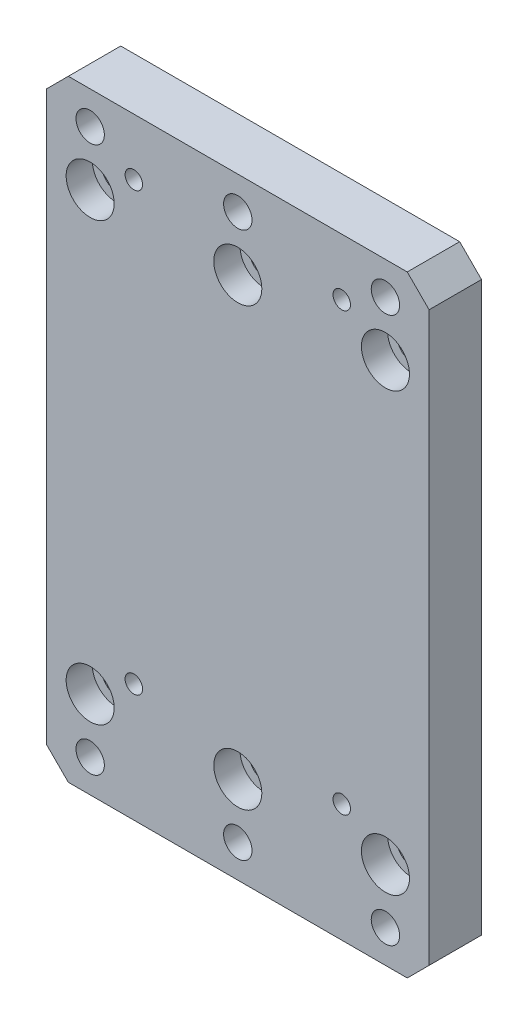
SolidWorks part; units mm, degrees
ref_plane "前视基准面" through (0, 0, 0) normal (0, 0, 1) x (1, 0, 0)
ref_plane "上视基准面" through (0, 0, 0) normal (0, 1, 0) x (1, 0, 0)
ref_plane "右视基准面" through (0, 0, 0) normal (1, 0, 0) x (0, 0, -1)
sketch "草图1" plane through (0, 0, 0) normal (0, 0, 1) x (1, 0, 0)
  line L1 (-43.8, -70) -> (43.8, -70)
  line L2 (-43.8, -70) -> (-43.8, 70)
  line L3 (-43.8, 70) -> (43.8, 70)
  line L4 (43.8, -70) -> (43.8, 70)
  line L5 (-43.8, -70) -> (43.8, 70) construction
  line L6 (-43.8, 70) -> (43.8, -70) construction
  point P0 (0, 0)
  dimension "D1" = 87.6
  dimension "D2" = 140
extrude "凸台-拉伸1" add sketch "草图1" along normal blind 12
chamfer "倒角1" distance 5 angle 45 4 edges at (-43.8, -70, 6) (43.8, -70, 6) (-43.8, 70, 6) (43.8, 70, 6)
hole_wizard "M6 六角凹头螺钉的柱形沉头孔1" positions "草图3" profile "草图2" counterbore size "M6" standard "ISO" end condition through all
sketch "草图3" plane through (0, 0, 12) normal (0, 0, 1) x (1, 0, 0)
  circle A0 centre (33.8, 50) radius 2.5 construction
  point P0 (33.8, 50)
  point P4 (0, 50)
  point P7 (-33.8, 50)
  point P10 (-33.8, -50)
  point P13 (0, -50)
  point P16 (33.8, -50)
sketch "草图2" plane through (33.8, 50, 12) normal (1, 0, 0) x (0, -1, 0)
  line L0 (0, 0) -> (0, 12)
  line L1 (0, 12) -> (3.3, 12)
  line L3 (3.3, 12) -> (3.3, 6)
  line L4 (3.3, 6) -> (5.5, 6)
  line L5 (5.5, 6) -> (5.5, 0)
  line L7 (5.5, 0) -> (0, 0)
  line L11 (0, -6.35) -> (0, 107.95) construction
  dimension "通孔孔直径" = 6.6
  dimension "通孔孔深度" = 12
  dimension "柱形沉头孔直径" = 11
  dimension "柱形沉头孔深度" = 6
sketch "草图4" plane through (0, 0, 12) normal (0, 0, 1) x (1, 0, 0)
  line L0 (-986.5861, 57) -> (49013.4139, 57) construction
  line L1 (-989.6693, -43) -> (49010.3307, -43) construction
  line L2 (23.8, -982.0225) -> (23.8, 49017.9775) construction
  line L3 (-23.8, -981.0975) -> (-23.8, 49018.9025) construction
  line L4 (43.8, -65) -> (43.8, 65) construction
  line L5 (-43.8, 65) -> (-43.8, -65) construction
  line L6 (-43.8013, 55) -> (43.8, 55) construction
  line L7 (-43.8013, -45) -> (43.8, -45) construction
  circle A0 centre (-23.8, 57) radius 2
  circle A1 centre (23.8, 57) radius 2
  circle A2 centre (23.8, -43) radius 2
  circle A3 centre (-23.8, -43) radius 2
  dimension "D5" = 4
  dimension "D1" = 20
  dimension "D2" = 20
  dimension "D3" = 2
  dimension "D4" = 2
extrude "切除-拉伸1" cut sketch "草图4" against normal through all
sketch "草图5" plane through (0, 0, 0) normal (0, 0, -1) x (-1, 0, 0)
  line L0 (-33.8, -992.5006) -> (-33.8, 49007.4994) construction
  line L1 (33.8, -998.6526) -> (33.8, 49001.3474) construction
  line L2 (-1007.13, 62.5) -> (48992.87, 62.5) construction
  line L3 (-1016.727, -62.5) -> (48983.273, -62.5) construction
  line L4 (43.8, 65) -> (43.8, -65) construction
  line L5 (-43.8, -65) -> (-43.8, 65) construction
  line L6 (-38.8, 70) -> (38.8, 70) construction
  line L7 (38.8, -70) -> (-38.8, -70) construction
  line L8 (0, -930) -> (0, 49070) construction
  circle A0 centre (33.8, 62.5) radius 3.25
  circle A1 centre (0, 62.5) radius 3.25
  circle A2 centre (-33.8, 62.5) radius 3.25
  circle A3 centre (33.8, -62.5) radius 3.25
  circle A4 centre (0, -62.5) radius 3.25
  circle A5 centre (-33.8, -62.5) radius 3.25
  point P19 (0, 70)
  dimension "D5" = 6.5
  dimension "D1" = 10
  dimension "D2" = 10
  dimension "D3" = 7.5
  dimension "D4" = 7.5
extrude "切除-拉伸2" cut sketch "草图5" against normal through all
